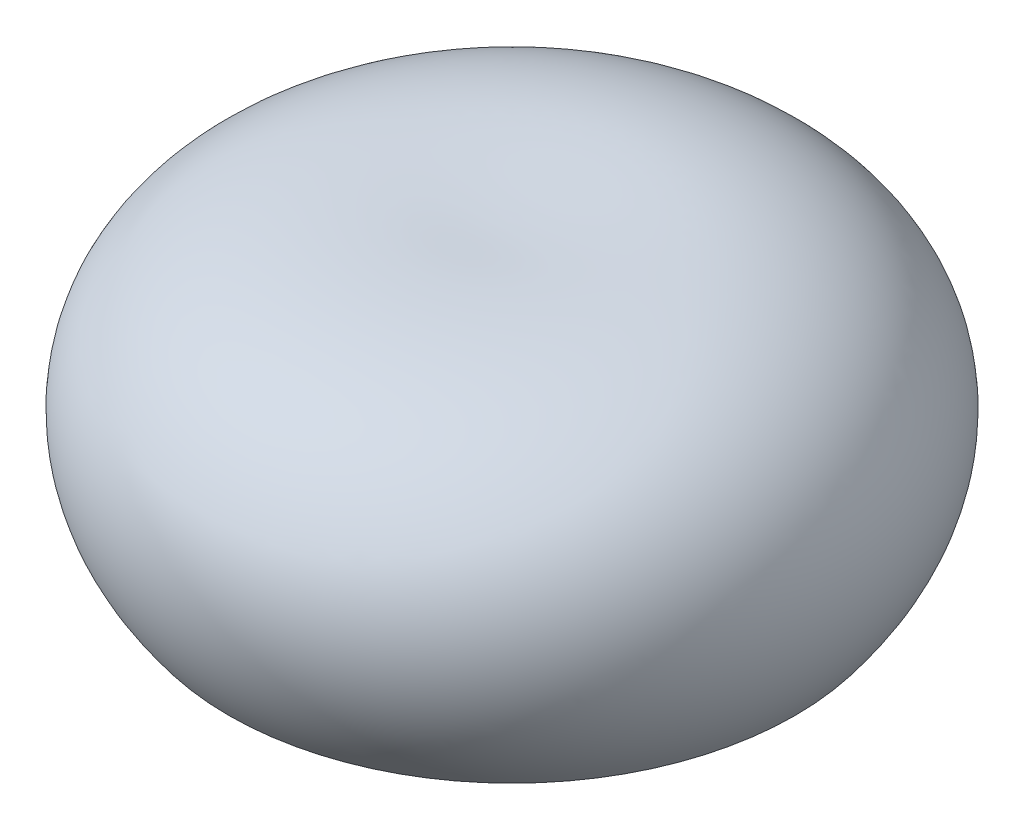
SolidWorks part; units mm, degrees
ref_plane "前视基准面" through (0, 0, 0) normal (0, 0, 1) x (1, 0, 0)
ref_plane "上视基准面" through (0, 0, 0) normal (0, 1, 0) x (1, 0, 0)
ref_plane "右视基准面" through (0, 0, 0) normal (1, 0, 0) x (0, 0, -1)
curve "曲线1"
  spline degree 3 poles (0, 7, 0) (0.0738, 6.9996, 0) (0.1783, 6.9991, 0) (0.3064, 7.0012, 0) (0.3805, 7.0029, 0) (0.4416, 7.0045, 0) (0.495, 7.0061, 0) (0.5432, 7.0077, 0) (0.5875, 7.0093, 0) (0.6288, 7.0109, 0) (0.6676, 7.0125, 0) (0.7044, 7.0141, 0) (0.7394, 7.0157, 0) (0.7729, 7.0172, 0) (0.8051, 7.0187, 0) (0.8362, 7.0203, 0) (0.8662, 7.0218, 0) (0.8953, 7.0233, 0) (0.9235, 7.0247, 0) (0.951, 7.0262, 0) (0.9778, 7.0276, 0) (1.004, 7.0291, 0) (1.0295, 7.0305, 0) (1.0545, 7.0319, 0) (1.079, 7.0333, 0) (1.103, 7.0346, 0) (1.1265, 7.036, 0) (1.1496, 7.0373, 0) (1.1724, 7.0386, 0) (1.1947, 7.0399, 0) (1.2167, 7.0412, 0) (1.2384, 7.0425, 0) (1.2598, 7.0438, 0) (1.2808, 7.045, 0) (1.3016, 7.0462, 0) (1.3221, 7.0474, 0) (1.3423, 7.0486, 0) (1.3623, 7.0498, 0) (1.382, 7.051, 0) (1.4015, 7.0521, 0) (1.4208, 7.0533, 0) (1.4399, 7.0544, 0) (1.4588, 7.0555, 0) (1.4775, 7.0566, 0) (1.496, 7.0577, 0) (1.5143, 7.0587, 0) (1.5324, 7.0598, 0) (1.5504, 7.0608, 0) (1.5682, 7.0618, 0) (1.5859, 7.0628, 0) (1.6034, 7.0638, 0) (1.6207, 7.0648, 0) (1.6379, 7.0657, 0) (1.655, 7.0667, 0) (1.672, 7.0676, 0) (1.6888, 7.0685, 0) (1.7054, 7.0694, 0) (1.722, 7.0703, 0) (1.7385, 7.0712, 0) (1.7548, 7.072, 0) (1.771, 7.0728, 0) (1.7871, 7.0737, 0) (1.8031, 7.0745, 0) (1.819, 7.0753, 0) (1.8348, 7.0761, 0) (1.8505, 7.0768, 0) (1.8661, 7.0776, 0) (1.8816, 7.0783, 0) (1.897, 7.079, 0) (1.9123, 7.0797, 0) (1.9275, 7.0804, 0) (1.9427, 7.0811, 0) (1.9578, 7.0818, 0) (1.9727, 7.0824, 0) (1.9876, 7.0831, 0) (2.0025, 7.0837, 0) (2.0172, 7.0843, 0) (2.0319, 7.0849, 0) (2.0465, 7.0855, 0) (2.061, 7.0861, 0) (2.0755, 7.0866, 0) (2.0899, 7.0872, 0) (2.1042, 7.0877, 0) (2.1184, 7.0882, 0) (2.1326, 7.0887, 0) (2.1468, 7.0892, 0) (2.1608, 7.0896, 0) (2.1748, 7.0901, 0) (2.1888, 7.0905, 0) (2.2027, 7.091, 0) (2.2165, 7.0914, 0) (2.2302, 7.0918, 0) (2.244, 7.0922, 0) (2.2576, 7.0925, 0) (2.2712, 7.0929, 0) (2.2848, 7.0933, 0) (2.2983, 7.0936, 0) (2.3117, 7.0939, 0) (2.3251, 7.0942, 0) (2.3385, 7.0945, 0) (2.3518, 7.0948, 0) (2.365, 7.095, 0) (2.3782, 7.0953, 0) (2.3914, 7.0955, 0) (2.4045, 7.0958, 0) (2.4175, 7.096, 0) (2.4305, 7.0962, 0) (2.4435, 7.0964, 0) (2.4565, 7.0965, 0) (2.4693, 7.0967, 0) (2.4822, 7.0968, 0) (2.495, 7.097, 0) (2.5078, 7.0971, 0) (2.5205, 7.0972, 0) (2.5332, 7.0973, 0) (2.5458, 7.0974, 0) (2.5584, 7.0974, 0) (2.571, 7.0975, 0) (2.5835, 7.0975, 0) (2.596, 7.0975, 0) (2.6085, 7.0975, 0) (2.6209, 7.0975, 0) (2.6333, 7.0975, 0) (2.6457, 7.0975, 0) (2.658, 7.0975, 0) (2.6703, 7.0974, 0) (2.6825, 7.0973, 0) (2.6948, 7.0973, 0) (2.7069, 7.0972, 0) (2.7191, 7.0971, 0) (2.7312, 7.0969, 0) (2.7433, 7.0968, 0) (2.7554, 7.0967, 0) (2.7674, 7.0965, 0) (2.7794, 7.0963, 0) (2.7914, 7.0962, 0) (2.8033, 7.096, 0) (2.8152, 7.0958, 0) (2.8271, 7.0955, 0) (2.8389, 7.0953, 0) (2.8508, 7.095, 0) (2.8625, 7.0948, 0) (2.8743, 7.0945, 0) (2.8861, 7.0942, 0) (2.8978, 7.0939, 0) (2.9094, 7.0936, 0) (2.9211, 7.0933, 0) (2.9327, 7.093, 0) (2.9443, 7.0926, 0) (2.9559, 7.0922, 0) (2.9675, 7.0919, 0) (2.979, 7.0915, 0) (2.9905, 7.0911, 0) (3.002, 7.0907, 0) (3.0134, 7.0902, 0) (3.0249, 7.0898, 0) (3.0363, 7.0893, 0) (3.0477, 7.0889, 0) (3.059, 7.0884, 0) (3.0704, 7.0879, 0) (3.0817, 7.0874, 0) (3.093, 7.0869, 0) (3.1042, 7.0864, 0) (3.1155, 7.0858, 0) (3.1267, 7.0853, 0) (3.1379, 7.0847, 0) (3.1491, 7.0841, 0) (3.1602, 7.0835, 0) (3.1714, 7.0829, 0) (3.1825, 7.0823, 0) (3.1936, 7.0817, 0) (3.2047, 7.0811, 0) (3.2157, 7.0804, 0) (3.2267, 7.0797, 0) (3.2378, 7.0791, 0) (3.2488, 7.0784, 0) (3.2597, 7.0777, 0) (3.2707, 7.0769, 0) (3.2816, 7.0762, 0) (3.2925, 7.0755, 0) (3.3034, 7.0747, 0) (3.3143, 7.074, 0) (3.3252, 7.0732, 0) (3.336, 7.0724, 0) (3.3468, 7.0716, 0) (3.3576, 7.0708, 0) (3.3684, 7.0699, 0) (3.3792, 7.0691, 0) (3.3899, 7.0683, 0) (3.4006, 7.0674, 0) (3.4113, 7.0665, 0) (3.422, 7.0656, 0) (3.4327, 7.0647, 0) (3.4434, 7.0638, 0) (3.454, 7.0629, 0) (3.4646, 7.0619, 0) (3.4752, 7.061, 0) (3.4858, 7.06, 0) (3.4964, 7.059, 0) (3.507, 7.0581, 0) (3.5175, 7.0571, 0) (3.528, 7.056, 0) (3.5385, 7.055, 0) (3.549, 7.054, 0) (3.5595, 7.0529, 0) (3.5699, 7.0519, 0) (3.5804, 7.0508, 0) (3.5908, 7.0497, 0) (3.6012, 7.0486, 0) (3.6116, 7.0475, 0) (3.622, 7.0464, 0) (3.6324, 7.0452, 0) (3.6427, 7.0441, 0) (3.6531, 7.0429, 0) (3.6634, 7.0417, 0) (3.6737, 7.0406, 0) (3.684, 7.0394, 0) (3.6942, 7.0381, 0) (3.7045, 7.0369, 0) (3.7148, 7.0357, 0) (3.725, 7.0344, 0) (3.7352, 7.0332, 0) (3.7454, 7.0319, 0) (3.7556, 7.0306, 0) (3.7658, 7.0293, 0) (3.7759, 7.028, 0) (3.7861, 7.0267, 0) (3.7962, 7.0254, 0) (3.8063, 7.024, 0) (3.8164, 7.0227, 0) (3.8265, 7.0213, 0) (3.8366, 7.0199, 0) (3.8467, 7.0185, 0) (3.8567, 7.0171, 0) (3.8668, 7.0157, 0) (3.8768, 7.0142, 0) (3.8868, 7.0128, 0) (3.8968, 7.0113, 0) (3.9068, 7.0099, 0) (3.9168, 7.0084, 0) (3.9267, 7.0069, 0) (3.9367, 7.0054, 0) (3.9466, 7.0039, 0) (3.9565, 7.0024, 0) (3.9665, 7.0008, 0) (3.9764, 6.9993, 0) (3.9862, 6.9977, 0) (3.9961, 6.9961, 0) (4.006, 6.9945, 0) (4.0158, 6.9929, 0) (4.0257, 6.9913, 0) (4.0355, 6.9897, 0) (4.0453, 6.988, 0) (4.0551, 6.9864, 0) (4.0649, 6.9847, 0) (4.0747, 6.983, 0) (4.0844, 6.9813, 0) (4.0942, 6.9796, 0) (4.1039, 6.9779, 0) (4.1136, 6.9762, 0) (4.1234, 6.9745, 0) (4.1331, 6.9727, 0) (4.1428, 6.971, 0) (4.1524, 6.9692, 0) (4.1621, 6.9674, 0) (4.1718, 6.9656, 0) (4.1814, 6.9638, 0) (4.1911, 6.962, 0) (4.2007, 6.9601, 0) (4.2103, 6.9583, 0) (4.2199, 6.9564, 0) (4.2295, 6.9545, 0) (4.2391, 6.9527, 0) (4.2486, 6.9508, 0) (4.2582, 6.9488, 0) (4.2677, 6.9469, 0) (4.2773, 6.945, 0) (4.2868, 6.943, 0) (4.2963, 6.9411, 0) (4.3058, 6.9391, 0) (4.3153, 6.9371, 0) (4.3248, 6.9351, 0) (4.3343, 6.9331, 0) (4.3437, 6.9311, 0) (4.3532, 6.9291, 0) (4.3626, 6.927, 0) (4.3721, 6.925, 0) (4.3815, 6.9229, 0) (4.3909, 6.9208, 0) (4.4003, 6.9187, 0) (4.4097, 6.9166, 0) (4.4191, 6.9145, 0) (4.4284, 6.9123, 0) (4.4378, 6.9102, 0) (4.4471, 6.908, 0) (4.4565, 6.9059, 0) (4.4658, 6.9037, 0) (4.4751, 6.9015, 0) (4.4844, 6.8993, 0) (4.4937, 6.8971, 0) (4.503, 6.8948, 0) (4.5123, 6.8926, 0) (4.5215, 6.8903, 0) (4.5308, 6.8881, 0) (4.54, 6.8858, 0) (4.5493, 6.8835, 0) (4.5585, 6.8812, 0) (4.5677, 6.8789, 0) (4.5769, 6.8765, 0) (4.5861, 6.8742, 0) (4.5953, 6.8718, 0) (4.6045, 6.8695, 0) (4.6136, 6.8671, 0) (4.6228, 6.8647, 0) (4.6319, 6.8623, 0) (4.6411, 6.8599, 0) (4.6502, 6.8575, 0) (4.6593, 6.855, 0) (4.6684, 6.8526, 0) (4.6775, 6.8501, 0) (4.6866, 6.8476, 0) (4.6957, 6.8451, 0) (4.7048, 6.8426, 0) (4.7138, 6.8401, 0) (4.7229, 6.8376, 0) (4.7319, 6.835, 0) (4.741, 6.8325, 0) (4.75, 6.8299, 0) (4.759, 6.8273, 0) (4.768, 6.8247, 0) (4.777, 6.8221, 0) (4.786, 6.8195, 0) (4.795, 6.8169, 0) (4.8039, 6.8142, 0) (4.8129, 6.8116, 0) (4.8218, 6.8089, 0) (4.8308, 6.8062, 0) (4.8397, 6.8035, 0) (4.8486, 6.8008, 0) (4.8575, 6.7981, 0) (4.8664, 6.7954, 0) (4.8753, 6.7926, 0) (4.8842, 6.7899, 0) (4.8931, 6.7871, 0) (4.902, 6.7843, 0) (4.9108, 6.7815, 0) (4.9197, 6.7787, 0) (4.9285, 6.7759, 0) (4.9373, 6.7731, 0) (4.9462, 6.7702, 0) (4.955, 6.7673, 0) (4.9638, 6.7645, 0) (4.9726, 6.7616, 0) (4.9813, 6.7587, 0) (4.9901, 6.7558, 0) (4.9989, 6.7529, 0) (5.0076, 6.7499, 0) (5.0164, 6.747, 0) (5.0251, 6.744, 0) (5.0339, 6.7411, 0) (5.0426, 6.7381, 0) (5.0513, 6.7351, 0) (5.06, 6.7321, 0) (5.0687, 6.729, 0) (5.0774, 6.726, 0) (5.0861, 6.7229, 0) (5.0947, 6.7199, 0) (5.1034, 6.7168, 0) (5.112, 6.7137, 0) (5.1207, 6.7106, 0) (5.1293, 6.7075, 0) (5.1379, 6.7044, 0) (5.1465, 6.7012, 0) (5.1552, 6.6981, 0) (5.1638, 6.6949, 0) (5.1723, 6.6917, 0) (5.1809, 6.6885, 0) (5.1895, 6.6853, 0) (5.1981, 6.6821, 0) (5.2066, 6.6789, 0) (5.2151, 6.6756, 0) (5.2237, 6.6724, 0) (5.2322, 6.6691, 0) (5.2407, 6.6658, 0) (5.2492, 6.6625, 0) (5.2577, 6.6592, 0) (5.2662, 6.6559, 0) (5.2747, 6.6526, 0) (5.2832, 6.6492, 0) (5.2917, 6.6459, 0) (5.3001, 6.6425, 0) (5.3086, 6.6391, 0) (5.317, 6.6357, 0) (5.3254, 6.6323, 0) (5.3338, 6.6289, 0) (5.3423, 6.6254, 0) (5.3507, 6.622, 0) (5.3591, 6.6185, 0) (5.3674, 6.615, 0) (5.3758, 6.6115, 0) (5.3842, 6.608, 0) (5.3926, 6.6045, 0) (5.4009, 6.601, 0) (5.4092, 6.5974, 0) (5.4176, 6.5939, 0) (5.4259, 6.5903, 0) (5.4342, 6.5867, 0) (5.4425, 6.5831, 0) (5.4508, 6.5795, 0) (5.4591, 6.5759, 0) (5.4674, 6.5722, 0) (5.4757, 6.5686, 0) (5.4839, 6.5649, 0) (5.4922, 6.5612, 0) (5.5004, 6.5576, 0) (5.5087, 6.5538, 0) (5.5169, 6.5501, 0) (5.5251, 6.5464, 0) (5.5333, 6.5427, 0) (5.5415, 6.5389, 0) (5.5497, 6.5351, 0) (5.5579, 6.5313, 0) (5.5661, 6.5275, 0) (5.5743, 6.5237, 0) (5.5824, 6.5199, 0) (5.5906, 6.5161, 0) (5.5987, 6.5122, 0) (5.6069, 6.5083, 0) (5.615, 6.5045, 0) (5.6231, 6.5006, 0) (5.6312, 6.4967, 0) (5.6393, 6.4927, 0) (5.6474, 6.4888, 0) (5.6555, 6.4849, 0) (5.6635, 6.4809, 0) (5.6716, 6.4769, 0) (5.6796, 6.4729, 0) (5.6877, 6.4689, 0) (5.6957, 6.4649, 0) (5.7038, 6.4609, 0) (5.7118, 6.4568, 0) (5.7198, 6.4528, 0) (5.7278, 6.4487, 0) (5.7358, 6.4446, 0) (5.7438, 6.4405, 0) (5.7517, 6.4364, 0) (5.7597, 6.4323, 0) (5.7676, 6.4282, 0) (5.7756, 6.424, 0) (5.7835, 6.4198, 0) (5.7915, 6.4157, 0) (5.7994, 6.4115, 0) (5.8073, 6.4073, 0) (5.8152, 6.403, 0) (5.8231, 6.3988, 0) (5.831, 6.3945, 0) (5.8388, 6.3903, 0) (5.8467, 6.386, 0) (5.8546, 6.3817, 0) (5.8624, 6.3774, 0) (5.8703, 6.3731, 0) (5.8781, 6.3687, 0) (5.8859, 6.3644, 0) (5.8937, 6.36, 0) (5.9015, 6.3557, 0) (5.9093, 6.3513, 0) (5.9171, 6.3469, 0) (5.9249, 6.3424, 0) (5.9326, 6.338, 0) (5.9404, 6.3336, 0) (5.9481, 6.3291, 0) (5.9559, 6.3246, 0) (5.9636, 6.3201, 0) (5.9713, 6.3156, 0) (5.979, 6.3111, 0) (5.9867, 6.3066, 0) (5.9944, 6.302, 0) (6.0021, 6.2975, 0) (6.0098, 6.2929, 0) (6.0175, 6.2883, 0) (6.0251, 6.2837, 0) (6.0328, 6.2791, 0) (6.0404, 6.2745, 0) (6.048, 6.2698, 0) (6.0556, 6.2652, 0) (6.0633, 6.2605, 0) (6.0709, 6.2558, 0) (6.0784, 6.2511, 0) (6.086, 6.2464, 0) (6.0936, 6.2416, 0) (6.1012, 6.2369, 0) (6.1087, 6.2321, 0) (6.1163, 6.2274, 0) (6.1238, 6.2226, 0) (6.1313, 6.2178, 0) (6.1388, 6.2129, 0) (6.1463, 6.2081, 0) (6.1538, 6.2033, 0) (6.1613, 6.1984, 0) (6.1688, 6.1935, 0) (6.1763, 6.1886, 0) (6.1837, 6.1837, 0) (6.1912, 6.1788, 0) (6.1986, 6.1739, 0) (6.206, 6.1689, 0) (6.2134, 6.1639, 0) (6.2208, 6.159, 0) (6.2282, 6.154, 0) (6.2356, 6.1489, 0) (6.243, 6.1439, 0) (6.2504, 6.1389, 0) (6.2577, 6.1338, 0) (6.2651, 6.1287, 0) (6.2724, 6.1237, 0) (6.2798, 6.1186, 0) (6.2871, 6.1134, 0) (6.2944, 6.1083, 0) (6.3017, 6.1032, 0) (6.309, 6.098, 0) (6.3163, 6.0928, 0) (6.3235, 6.0876, 0) (6.3308, 6.0824, 0) (6.3381, 6.0772, 0) (6.3453, 6.072, 0) (6.3525, 6.0667, 0) (6.3598, 6.0615, 0) (6.367, 6.0562, 0) (6.3742, 6.0509, 0) (6.3814, 6.0456, 0) (6.3885, 6.0403, 0) (6.3957, 6.0349, 0) (6.4029, 6.0296, 0) (6.41, 6.0242, 0) (6.4172, 6.0188, 0) (6.4243, 6.0134, 0) (6.4314, 6.008, 0) (6.4385, 6.0025, 0) (6.4456, 5.9971, 0) (6.4527, 5.9916, 0) (6.4598, 5.9861, 0) (6.4668, 5.9806, 0) (6.4739, 5.9751, 0) (6.4809, 5.9696, 0) (6.488, 5.9641, 0) (6.495, 5.9585, 0) (6.502, 5.9529, 0) (6.509, 5.9473, 0) (6.516, 5.9417, 0) (6.523, 5.9361, 0) (6.53, 5.9305, 0) (6.5369, 5.9248, 0) (6.5439, 5.9192, 0) (6.5508, 5.9135, 0) (6.5578, 5.9078, 0) (6.5647, 5.9021, 0) (6.5716, 5.8963, 0) (6.5785, 5.8906, 0) (6.5854, 5.8848, 0) (6.5922, 5.8791, 0) (6.5991, 5.8733, 0) (6.606, 5.8675, 0) (6.6128, 5.8616, 0) (6.6196, 5.8558, 0) (6.6265, 5.8499, 0) (6.6333, 5.8441, 0) (6.6401, 5.8382, 0) (6.6469, 5.8323, 0) (6.6536, 5.8263, 0) (6.6604, 5.8204, 0) (6.6672, 5.8144, 0) (6.6739, 5.8085, 0) (6.6806, 5.8025, 0) (6.6874, 5.7965, 0) (6.6941, 5.7905, 0) (6.7008, 5.7844, 0) (6.7074, 5.7784, 0) (6.7141, 5.7723, 0) (6.7208, 5.7662, 0) (6.7274, 5.7601, 0) (6.7341, 5.754, 0) (6.7407, 5.7479, 0) (6.7473, 5.7417, 0) (6.7539, 5.7356, 0) (6.7605, 5.7294, 0) (6.7671, 5.7232, 0) (6.7737, 5.717, 0) (6.7802, 5.7107, 0) (6.7868, 5.7045, 0) (6.7933, 5.6982, 0) (6.7998, 5.6919, 0) (6.8064, 5.6856, 0) (6.8129, 5.6793, 0) (6.8194, 5.673, 0) (6.8258, 5.6666, 0) (6.8323, 5.6603, 0) (6.8387, 5.6539, 0) (6.8452, 5.6475, 0) (6.8516, 5.6411, 0) (6.858, 5.6346, 0) (6.8644, 5.6282, 0) (6.8708, 5.6217, 0) (6.8772, 5.6152, 0) (6.8836, 5.6087, 0) (6.8899, 5.6022, 0) (6.8963, 5.5957, 0) (6.9026, 5.5891, 0) (6.9089, 5.5825, 0) (6.9152, 5.5759, 0) (6.9215, 5.5693, 0) (6.9278, 5.5627, 0) (6.9341, 5.5561, 0) (6.9403, 5.5494, 0) (6.9466, 5.5427, 0) (6.9528, 5.5361, 0) (6.959, 5.5293, 0) (6.9652, 5.5226, 0) (6.9714, 5.5159, 0) (6.9776, 5.5091, 0) (6.9838, 5.5023, 0) (6.9899, 5.4955, 0) (6.9961, 5.4887, 0) (7.0022, 5.4819, 0) (7.0083, 5.475, 0) (7.0144, 5.4682, 0) (7.0205, 5.4613, 0) (7.0266, 5.4544, 0) (7.0326, 5.4475, 0) (7.0387, 5.4405, 0) (7.0447, 5.4336, 0) (7.0507, 5.4266, 0) (7.0568, 5.4196, 0) (7.0627, 5.4126, 0) (7.0687, 5.4055, 0) (7.0747, 5.3985, 0) (7.0807, 5.3914, 0) (7.0866, 5.3844, 0) (7.0925, 5.3772, 0) (7.0984, 5.3701, 0) (7.1043, 5.363, 0) (7.1102, 5.3558, 0) (7.1161, 5.3487, 0) (7.122, 5.3415, 0) (7.1278, 5.3343, 0) (7.1336, 5.327, 0) (7.1395, 5.3198, 0) (7.1453, 5.3125, 0) (7.151, 5.3052, 0) (7.1568, 5.2979, 0) (7.1626, 5.2906, 0) (7.1683, 5.2833, 0) (7.1741, 5.2759, 0) (7.1798, 5.2685, 0) (7.1855, 5.2611, 0) (7.1912, 5.2537, 0) (7.1968, 5.2463, 0) (7.2025, 5.2388, 0) (7.2082, 5.2313, 0) (7.2138, 5.2238, 0) (7.2194, 5.2163, 0) (7.225, 5.2088, 0) (7.2306, 5.2013, 0) (7.2362, 5.1937, 0) (7.2417, 5.1861, 0) (7.2473, 5.1785, 0) (7.2528, 5.1709, 0) (7.2583, 5.1632, 0) (7.2638, 5.1556, 0) (7.2693, 5.1479, 0) (7.2748, 5.1402, 0) (7.2802, 5.1324, 0) (7.2856, 5.1247, 0) (7.2911, 5.1169, 0) (7.2965, 5.1092, 0) (7.3019, 5.1014, 0) (7.3072, 5.0935, 0) (7.3126, 5.0857, 0) (7.3179, 5.0778, 0) (7.3233, 5.0699, 0) (7.3286, 5.062, 0) (7.3339, 5.0541, 0) (7.3391, 5.0462, 0) (7.3444, 5.0382, 0) (7.3497, 5.0302, 0) (7.3549, 5.0222, 0) (7.3601, 5.0142, 0) (7.3653, 5.0062, 0) (7.3705, 4.9981, 0) (7.3757, 4.99, 0) (7.3808, 4.9819, 0) (7.3859, 4.9738, 0) (7.3911, 4.9657, 0) (7.3962, 4.9575, 0) (7.4012, 4.9493, 0) (7.4063, 4.9411, 0) (7.4114, 4.9329, 0) (7.4164, 4.9246, 0) (7.4214, 4.9164, 0) (7.4264, 4.9081, 0) (7.4314, 4.8998, 0) (7.4364, 4.8914, 0) (7.4413, 4.8831, 0) (7.4462, 4.8747, 0) (7.4512, 4.8663, 0) (7.4561, 4.8579, 0) (7.4609, 4.8495, 0) (7.4658, 4.841, 0) (7.4706, 4.8325, 0) (7.4755, 4.824, 0) (7.4803, 4.8155, 0) (7.4851, 4.807, 0) (7.4899, 4.7984, 0) (7.4946, 4.7898, 0) (7.4993, 4.7812, 0) (7.5041, 4.7726, 0) (7.5088, 4.7639, 0) (7.5134, 4.7552, 0) (7.5181, 4.7465, 0) (7.5228, 4.7378, 0) (7.5274, 4.7291, 0) (7.532, 4.7203, 0) (7.5366, 4.7115, 0) (7.5412, 4.7027, 0) (7.5457, 4.6939, 0) (7.5503, 4.6851, 0) (7.5548, 4.6762, 0) (7.5593, 4.6673, 0) (7.5637, 4.6584, 0) (7.5682, 4.6494, 0) (7.5726, 4.6405, 0) (7.5771, 4.6315, 0) (7.5815, 4.6225, 0) (7.5858, 4.6134, 0) (7.5902, 4.6044, 0) (7.5945, 4.5953, 0) (7.5989, 4.5862, 0) (7.6032, 4.5771, 0) (7.6075, 4.5679, 0) (7.6117, 4.5587, 0) (7.616, 4.5495, 0) (7.6202, 4.5403, 0) (7.6244, 4.5311, 0) (7.6286, 4.5218, 0) (7.6327, 4.5125, 0) (7.6369, 4.5032, 0) (7.641, 4.4939, 0) (7.6451, 4.4845, 0) (7.6492, 4.4751, 0) (7.6532, 4.4657, 0) (7.6573, 4.4563, 0) (7.6613, 4.4468, 0) (7.6653, 4.4373, 0) (7.6692, 4.4278, 0) (7.6732, 4.4183, 0) (7.6771, 4.4087, 0) (7.681, 4.3992, 0) (7.6849, 4.3896, 0) (7.6888, 4.3799, 0) (7.6926, 4.3703, 0) (7.6964, 4.3606, 0) (7.7002, 4.3509, 0) (7.704, 4.3411, 0) (7.7078, 4.3314, 0) (7.7115, 4.3216, 0) (7.7152, 4.3118, 0) (7.7189, 4.302, 0) (7.7226, 4.2921, 0) (7.7262, 4.2822, 0) (7.7298, 4.2723, 0) (7.7334, 4.2624, 0) (7.737, 4.2524, 0) (7.7405, 4.2424, 0) (7.744, 4.2324, 0) (7.7475, 4.2223, 0) (7.751, 4.2123, 0) (7.7545, 4.2022, 0) (7.7579, 4.1921, 0) (7.7613, 4.1819, 0) (7.7647, 4.1717, 0) (7.768, 4.1615, 0) (7.7714, 4.1513, 0) (7.7747, 4.141, 0) (7.778, 4.1308, 0) (7.7812, 4.1204, 0) (7.7845, 4.1101, 0) (7.7877, 4.0997, 0) (7.7908, 4.0893, 0) (7.794, 4.0789, 0) (7.7971, 4.0685, 0) (7.8002, 4.058, 0) (7.8033, 4.0475, 0) (7.8064, 4.0369, 0) (7.8094, 4.0264, 0) (7.8124, 4.0158, 0) (7.8154, 4.0051, 0) (7.8183, 3.9945, 0) (7.8212, 3.9838, 0) (7.8241, 3.9731, 0) (7.827, 3.9624, 0) (7.8298, 3.9516, 0) (7.8327, 3.9408, 0) (7.8354, 3.93, 0) (7.8382, 3.9191, 0) (7.8409, 3.9082, 0) (7.8436, 3.8973, 0) (7.8463, 3.8863, 0) (7.849, 3.8754, 0) (7.8516, 3.8643, 0) (7.8542, 3.8533, 0) (7.8567, 3.8422, 0) (7.8593, 3.8311, 0) (7.8618, 3.82, 0) (7.8642, 3.8088, 0) (7.8667, 3.7976, 0) (7.8691, 3.7864, 0) (7.8715, 3.7751, 0) (7.8738, 3.7638, 0) (7.8762, 3.7525, 0) (7.8785, 3.7411, 0) (7.8807, 3.7297, 0) (7.883, 3.7183, 0) (7.8852, 3.7069, 0) (7.8873, 3.6954, 0) (7.8895, 3.6838, 0) (7.8916, 3.6723, 0) (7.8937, 3.6607, 0) (7.8957, 3.6491, 0) (7.8977, 3.6374, 0) (7.8997, 3.6257, 0) (7.9016, 3.614, 0) (7.9036, 3.6022, 0) (7.9054, 3.5904, 0) (7.9073, 3.5786, 0) (7.9091, 3.5667, 0) (7.9109, 3.5548, 0) (7.9126, 3.5429, 0) (7.9144, 3.5309, 0) (7.916, 3.5189, 0) (7.9177, 3.5068, 0) (7.9193, 3.4947, 0) (7.9209, 3.4826, 0) (7.9224, 3.4705, 0) (7.9239, 3.4583, 0) (7.9254, 3.446, 0) (7.9268, 3.4338, 0) (7.9282, 3.4214, 0) (7.9296, 3.4091, 0) (7.9309, 3.3967, 0) (7.9322, 3.3843, 0) (7.9334, 3.3718, 0) (7.9346, 3.3593, 0) (7.9358, 3.3468, 0) (7.9369, 3.3342, 0) (7.938, 3.3215, 0) (7.9391, 3.3089, 0) (7.9401, 3.2962, 0) (7.9411, 3.2834, 0) (7.942, 3.2706, 0) (7.9429, 3.2578, 0) (7.9438, 3.2449, 0) (7.9446, 3.232, 0) (7.9454, 3.219, 0) (7.9461, 3.206, 0) (7.9468, 3.193, 0) (7.9475, 3.1799, 0) (7.9481, 3.1668, 0) (7.9486, 3.1536, 0) (7.9492, 3.1403, 0) (7.9496, 3.1271, 0) (7.9501, 3.1138, 0) (7.9505, 3.1004, 0) (7.9508, 3.087, 0) (7.9511, 3.0735, 0) (7.9514, 3.06, 0) (7.9516, 3.0465, 0) (7.9517, 3.0329, 0) (7.9518, 3.0192, 0) (7.9519, 3.0055, 0) (7.9519, 2.9918, 0) (7.9519, 2.978, 0) (7.9518, 2.9641, 0) (7.9517, 2.9502, 0) (7.9515, 2.9363, 0) (7.9513, 2.9223, 0) (7.951, 2.9082, 0) (7.9507, 2.8941, 0) (7.9503, 2.88, 0) (7.9499, 2.8657, 0) (7.9494, 2.8515, 0) (7.9489, 2.8371, 0) (7.9483, 2.8228, 0) (7.9477, 2.8083, 0) (7.947, 2.7938, 0) (7.9462, 2.7793, 0) (7.9454, 2.7647, 0) (7.9445, 2.75, 0) (7.9436, 2.7353, 0) (7.9426, 2.7205, 0) (7.9416, 2.7056, 0) (7.9405, 2.6907, 0) (7.9393, 2.6757, 0) (7.9381, 2.6607, 0) (7.9368, 2.6456, 0) (7.9355, 2.6304, 0) (7.9341, 2.6152, 0) (7.9326, 2.5999, 0) (7.9311, 2.5845, 0) (7.9295, 2.5691, 0) (7.9278, 2.5536, 0) (7.9261, 2.538, 0) (7.9243, 2.5224, 0) (7.9224, 2.5066, 0) (7.9205, 2.4909, 0) (7.9185, 2.475, 0) (7.9164, 2.459, 0) (7.9143, 2.443, 0) (7.912, 2.4269, 0) (7.9097, 2.4108, 0) (7.9074, 2.3945, 0) (7.9049, 2.3782, 0) (7.9024, 2.3618, 0) (7.8998, 2.3453, 0) (7.8971, 2.3287, 0) (7.8943, 2.312, 0) (7.8915, 2.2953, 0) (7.8885, 2.2784, 0) (7.8855, 2.2615, 0) (7.8824, 2.2445, 0) (7.8792, 2.2273, 0) (7.8759, 2.2101, 0) (7.8725, 2.1928, 0) (7.8691, 2.1754, 0) (7.8655, 2.1579, 0) (7.8618, 2.1403, 0) (7.8581, 2.1225, 0) (7.8542, 2.1047, 0) (7.8503, 2.0868, 0) (7.8462, 2.0687, 0) (7.842, 2.0506, 0) (7.8378, 2.0323, 0) (7.8334, 2.0139, 0) (7.8289, 1.9954, 0) (7.8243, 1.9767, 0) (7.8195, 1.9579, 0) (7.8147, 1.939, 0) (7.8097, 1.92, 0) (7.8046, 1.9008, 0) (7.7994, 1.8815, 0) (7.794, 1.8621, 0) (7.7885, 1.8425, 0) (7.7829, 1.8227, 0) (7.7771, 1.8028, 0) (7.7712, 1.7828, 0) (7.7652, 1.7626, 0) (7.759, 1.7422, 0) (7.7526, 1.7216, 0) (7.7461, 1.7009, 0) (7.7394, 1.6799, 0) (7.7325, 1.6588, 0) (7.7255, 1.6375, 0) (7.7182, 1.616, 0) (7.7108, 1.5943, 0) (7.7032, 1.5723, 0) (7.6954, 1.5502, 0) (7.6874, 1.5278, 0) (7.6792, 1.5051, 0) (7.6708, 1.4822, 0) (7.6621, 1.4591, 0) (7.6532, 1.4357, 0) (7.644, 1.412, 0) (7.6346, 1.388, 0) (7.6249, 1.3637, 0) (7.615, 1.3391, 0) (7.6047, 1.3141, 0) (7.5941, 1.2888, 0) (7.5833, 1.2631, 0) (7.572, 1.237, 0) (7.5604, 1.2105, 0) (7.5485, 1.1835, 0) (7.5361, 1.1561, 0) (7.5233, 1.1282, 0) (7.51, 1.0997, 0) (7.4963, 1.0707, 0) (7.482, 1.041, 0) (7.4672, 1.0107, 0) (7.4518, 0.9797, 0) (7.4357, 0.9478, 0) (7.4189, 0.9152, 0) (7.4013, 0.8815, 0) (7.3829, 0.8469, 0) (7.3635, 0.811, 0) (7.343, 0.7739, 0) (7.3212, 0.7352, 0) (7.2981, 0.6948, 0) (7.2732, 0.6523, 0) (7.2464, 0.6073, 0) (7.2172, 0.5594, 0) (7.1849, 0.5076, 0) (7.1485, 0.4506, 0) (7.1062, 0.386, 0) (7.0539, 0.3086, 0) (6.9626, 0.1779, 0) (6.8856, 0.0734, 0) (6.8314, 0, 0) knots 0 0 0 0 0.016508 0.023364 0.028636 0.033092 0.037026 0.040591 0.043877 0.046942 0.049828 0.052563 0.055171 0.057668 0.060068 0.062382 0.06462 0.066789 0.068896 0.070946 0.072944 0.074894 0.0768 0.078664 0.080491 0.082282 0.08404 0.085766 0.087463 0.089131 0.090774 0.092392 0.093986 0.095557 0.097107 0.098637 0.100147 0.101639 0.103112 0.104569 0.10601 0.107434 0.108844 0.110239 0.11162 0.112987 0.114341 0.115683 0.117013 0.118331 0.119637 0.120933 0.122218 0.123492 0.124757 0.126012 0.127257 0.128493 0.129721 0.130939 0.132149 0.133351 0.134545 0.135731 0.13691 0.138081 0.139245 0.140402 0.141552 0.142695 0.143832 0.144962 0.146086 0.147204 0.148315 0.149421 0.150522 0.151616 0.152705 0.153789 0.154868 0.155941 0.157009 0.158072 0.159131 0.160184 0.161233 0.162277 0.163317 0.164352 0.165383 0.16641 0.167433 0.168451 0.169465 0.170476 0.171482 0.172485 0.173483 0.174478 0.17547 0.176457 0.177442 0.178422 0.1794 0.180374 0.181344 0.182312 0.183276 0.184236 0.185194 0.186149 0.187101 0.188049 0.188995 0.189938 0.190877 0.191815 0.192749 0.19368 0.194609 0.195535 0.196459 0.19738 0.198298 0.199214 0.200127 0.201038 0.201946 0.202852 0.203756 0.204657 0.205556 0.206453 0.207347 0.208239 0.209129 0.210017 0.210902 0.211786 0.212667 0.213547 0.214424 0.215299 0.216172 0.217044 0.217913 0.21878 0.219646 0.220509 0.221371 0.222231 0.223089 0.223945 0.2248 0.225652 0.226503 0.227353 0.2282 0.229046 0.22989 0.230732 0.231573 0.232412 0.23325 0.234086 0.23492 0.235753 0.236585 0.237414 0.238243 0.239069 0.239895 0.240719 0.241541 0.242362 0.243182 0.244 0.244816 0.245632 0.246446 0.247258 0.24807 0.24888 0.249688 0.250496 0.251302 0.252106 0.25291 0.253712 0.254513 0.255313 0.256111 0.256909 0.257705 0.2585 0.259294 0.260086 0.260878 0.261668 0.262457 0.263245 0.264032 0.264818 0.265603 0.266386 0.267169 0.26795 0.268731 0.26951 0.270288 0.271066 0.271842 0.272617 0.273391 0.274165 0.274937 0.275708 0.276478 0.277248 0.278016 0.278784 0.27955 0.280316 0.28108 0.281844 0.282607 0.283369 0.28413 0.28489 0.285649 0.286407 0.287165 0.287921 0.288677 0.289432 0.290186 0.290939 0.291692 0.292444 0.293194 0.293944 0.294693 0.295442 0.296189 0.296936 0.297682 0.298428 0.299172 0.299916 0.300659 0.301401 0.302143 0.302883 0.303624 0.304363 0.305101 0.305839 0.306577 0.307313 0.308049 0.308784 0.309518 0.310252 0.310985 0.311718 0.312449 0.31318 0.313911 0.31464 0.31537 0.316098 0.316826 0.317553 0.31828 0.319006 0.319731 0.320456 0.32118 0.321903 0.322626 0.323349 0.32407 0.324791 0.325512 0.326232 0.326951 0.32767 0.328389 0.329106 0.329824 0.33054 0.331256 0.331972 0.332687 0.333401 0.334115 0.334829 0.335541 0.336254 0.336966 0.337677 0.338388 0.339098 0.339808 0.340517 0.341226 0.341934 0.342642 0.34335 0.344057 0.344763 0.345469 0.346174 0.346879 0.347584 0.348288 0.348992 0.349695 0.350398 0.3511 0.351802 0.352503 0.353204 0.353905 0.354605 0.355305 0.356004 0.356703 0.357401 0.3581 0.358797 0.359494 0.360191 0.360888 0.361584 0.362279 0.362975 0.36367 0.364364 0.365058 0.365752 0.366445 0.367138 0.367831 0.368523 0.369215 0.369907 0.370598 0.371289 0.371979 0.372669 0.373359 0.374049 0.374738 0.375427 0.376115 0.376803 0.377491 0.378178 0.378866 0.379552 0.380239 0.380925 0.381611 0.382297 0.382982 0.383667 0.384351 0.385036 0.38572 0.386404 0.387087 0.38777 0.388453 0.389136 0.389818 0.3905 0.391182 0.391863 0.392545 0.393226 0.393906 0.394587 0.395267 0.395947 0.396627 0.397306 0.397985 0.398664 0.399343 0.400021 0.400699 0.401377 0.402055 0.402733 0.40341 0.404087 0.404764 0.40544 0.406117 0.406793 0.407469 0.408144 0.40882 0.409495 0.41017 0.410845 0.41152 0.412194 0.412868 0.413542 0.414216 0.41489 0.415563 0.416237 0.41691 0.417583 0.418255 0.418928 0.4196 0.420273 0.420945 0.421616 0.422288 0.42296 0.423631 0.424302 0.424973 0.425644 0.426315 0.426986 0.427656 0.428326 0.428997 0.429667 0.430336 0.431006 0.431676 0.432345 0.433015 0.433684 0.434353 0.435022 0.435691 0.436359 0.437028 0.437696 0.438365 0.439033 0.439701 0.440369 0.441037 0.441705 0.442373 0.44304 0.443708 0.444375 0.445043 0.44571 0.446377 0.447044 0.447711 0.448378 0.449045 0.449711 0.450378 0.451045 0.451711 0.452378 0.453044 0.45371 0.454377 0.455043 0.455709 0.456375 0.457041 0.457707 0.458373 0.459039 0.459705 0.460371 0.461036 0.461702 0.462368 0.463034 0.463699 0.464365 0.46503 0.465696 0.466361 0.467027 0.467692 0.468358 0.469023 0.469689 0.470354 0.47102 0.471685 0.472351 0.473016 0.473681 0.474347 0.475012 0.475678 0.476343 0.477009 0.477674 0.47834 0.479005 0.479671 0.480336 0.481002 0.481668 0.482333 0.482999 0.483665 0.48433 0.484996 0.485662 0.486328 0.486994 0.48766 0.488326 0.488992 0.489658 0.490324 0.490991 0.491657 0.492324 0.49299 0.493657 0.494323 0.49499 0.495657 0.496324 0.496991 0.497658 0.498325 0.498992 0.499659 0.500327 0.500994 0.501662 0.50233 0.502997 0.503665 0.504333 0.505001 0.50567 0.506338 0.507007 0.507675 0.508344 0.509013 0.509682 0.510351 0.511021 0.51169 0.51236 0.513029 0.513699 0.514369 0.515039 0.51571 0.51638 0.517051 0.517722 0.518393 0.519064 0.519735 0.520407 0.521078 0.52175 0.522422 0.523095 0.523767 0.52444 0.525113 0.525786 0.526459 0.527132 0.527806 0.52848 0.529154 0.529828 0.530502 0.531177 0.531852 0.532527 0.533203 0.533878 0.534554 0.53523 0.535907 0.536583 0.53726 0.537937 0.538614 0.539292 0.53997 0.540648 0.541327 0.542005 0.542684 0.543363 0.544043 0.544723 0.545403 0.546083 0.546764 0.547445 0.548126 0.548808 0.549489 0.550172 0.550854 0.551537 0.55222 0.552904 0.553587 0.554271 0.554956 0.555641 0.556326 0.557011 0.557697 0.558383 0.55907 0.559757 0.560444 0.561132 0.56182 0.562508 0.563197 0.563886 0.564576 0.565266 0.565956 0.566647 0.567338 0.568029 0.568721 0.569414 0.570107 0.5708 0.571493 0.572188 0.572882 0.573577 0.574272 0.574968 0.575665 0.576361 0.577059 0.577756 0.578454 0.579153 0.579852 0.580552 0.581252 0.581952 0.582653 0.583355 0.584057 0.58476 0.585463 0.586166 0.586871 0.587575 0.58828 0.588986 0.589692 0.590399 0.591107 0.591815 0.592523 0.593232 0.593942 0.594652 0.595363 0.596074 0.596786 0.597499 0.598212 0.598926 0.59964 0.600355 0.601071 0.601787 0.602504 0.603222 0.60394 0.604659 0.605379 0.606099 0.60682 0.607541 0.608264 0.608987 0.60971 0.610435 0.61116 0.611885 0.612612 0.613339 0.614067 0.614796 0.615525 0.616255 0.616986 0.617718 0.61845 0.619183 0.619917 0.620652 0.621388 0.622124 0.622861 0.623599 0.624338 0.625078 0.625818 0.62656 0.627302 0.628045 0.628789 0.629534 0.630279 0.631026 0.631773 0.632522 0.633271 0.634021 0.634772 0.635524 0.636277 0.637031 0.637786 0.638542 0.639299 0.640056 0.640815 0.641575 0.642336 0.643098 0.64386 0.644624 0.645389 0.646155 0.646922 0.64769 0.648459 0.64923 0.650001 0.650773 0.651547 0.652322 0.653098 0.653875 0.654653 0.655432 0.656212 0.656994 0.657777 0.658561 0.659346 0.660133 0.66092 0.661709 0.662499 0.663291 0.664084 0.664878 0.665673 0.66647 0.667268 0.668067 0.668868 0.66967 0.670473 0.671278 0.672084 0.672892 0.673701 0.674511 0.675323 0.676136 0.676951 0.677768 0.678585 0.679405 0.680225 0.681048 0.681872 0.682697 0.683524 0.684353 0.685183 0.686015 0.686849 0.687684 0.688521 0.689359 0.690199 0.691041 0.691885 0.692731 0.693578 0.694427 0.695278 0.69613 0.696985 0.697841 0.698699 0.699559 0.700421 0.701285 0.702151 0.703018 0.703888 0.70476 0.705634 0.706509 0.707387 0.708267 0.709149 0.710033 0.710919 0.711808 0.712698 0.713591 0.714486 0.715384 0.716283 0.717185 0.718089 0.718996 0.719905 0.720816 0.721729 0.722646 0.723564 0.724485 0.725409 0.726335 0.727264 0.728195 0.729129 0.730066 0.731005 0.731947 0.732892 0.733839 0.734789 0.735743 0.736699 0.737658 0.738619 0.739584 0.740552 0.741523 0.742497 0.743474 0.744454 0.745438 0.746424 0.747414 0.748407 0.749404 0.750404 0.751407 0.752414 0.753424 0.754438 0.755455 0.756476 0.757501 0.758529 0.759562 0.760598 0.761638 0.762681 0.763729 0.764781 0.765837 0.766897 0.767962 0.76903 0.770103 0.77118 0.772262 0.773348 0.774439 0.775534 0.776634 0.777739 0.778849 0.779963 0.781083 0.782208 0.783337 0.784472 0.785613 0.786758 0.787909 0.789066 0.790228 0.791396 0.79257 0.79375 0.794936 0.796128 0.797326 0.79853 0.799741 0.800959 0.802183 0.803414 0.804652 0.805897 0.807149 0.808408 0.809675 0.81095 0.812232 0.813522 0.814821 0.816127 0.817442 0.818765 0.820098 0.821439 0.822789 0.824149 0.825518 0.826897 0.828286 0.829685 0.831095 0.832516 0.833947 0.83539 0.836844 0.83831 0.839789 0.841279 0.842783 0.8443 0.84583 0.847375 0.848933 0.850507 0.852096 0.8537 0.855321 0.856959 0.858613 0.860286 0.861977 0.863688 0.865418 0.867169 0.868942 0.870736 0.872554 0.874396 0.876263 0.878157 0.880078 0.882027 0.884007 0.886019 0.888063 0.890143 0.89226 0.894416 0.896614 0.898856 0.901145 0.903484 0.905877 0.908328 0.910841 0.913422 0.916077 0.918813 0.921638 0.924562 0.927596 0.930754 0.934054 0.937517 0.941171 0.945054 0.949215 0.953729 0.958707 0.964338 0.970988 0.979601 1 1 1 1
sketch "草图1" plane through (0, 0, 0) normal (0, 0, 1) x (1, 0, 0)
  line L0 (0, 7) -> (0, 0)
  line L1 (6.8314, 0) -> (0, 0)
  spline S0 degree 3 number of poles 1003 (0, 7) -> (6.8314, 0) construction
  spline S1 degree 3 number of poles 1003 (0, 7) -> (6.8314, 0)
revolve "旋转1" add sketch "草图1" angle 360 about L0
sketch "草图2" plane through (0, 0, 0) normal (0, -1, 0) x (1, 0, 0)
  line L0 (0, 3) -> (0, -3)
  arc A0 (0, -3) -> (0, 3) centre (0, 0) ccw
revolve "切除-旋转1" cut sketch "草图2" angle 360 about L0
